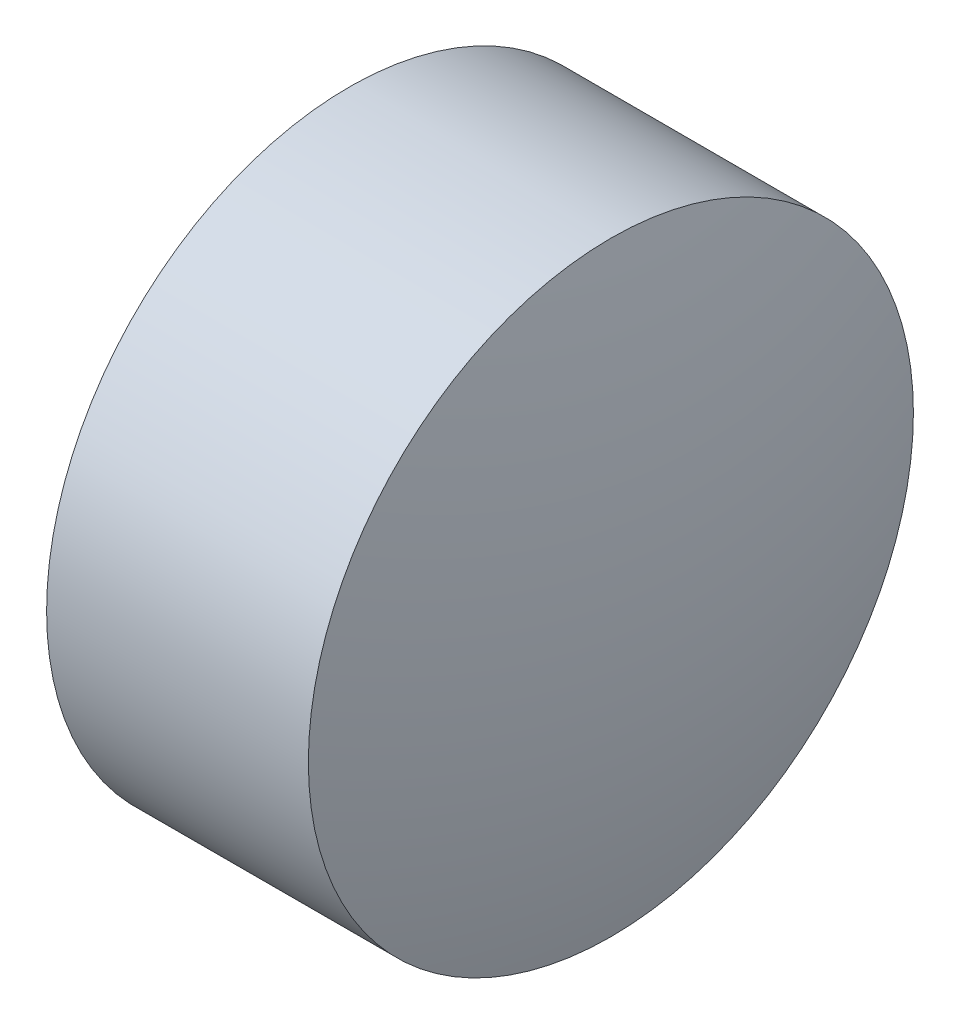
SolidWorks part; units mm, degrees
material "Glass"
ref_plane "Front Plane" through (0, 0, 0) normal (0, 0, 1) x (1, 0, 0)
ref_plane "Top Plane" through (0, 0, 0) normal (0, 1, 0) x (1, 0, 0)
ref_plane "Right Plane" through (0, 0, 0) normal (1, 0, 0) x (0, 0, -1)
sketch "Sketch1" plane through (0, 0, 0) normal (0, 0, 1) x (1, 0, 0)
  line L0 (-0.5, 0) -> (0.5, 0)
  line L2 (-0.5, 0) -> (-0.5, 1)
  line L3 (-0.5, 1) -> (0.3653, 1)
  arc A0 (0.5, 0) -> (0.3653, 1) centre (-3.278, 0) ccw
  point P0 (0, 0)
revolve "Revolve2" add sketch "Sketch1" angle 360 about L0
